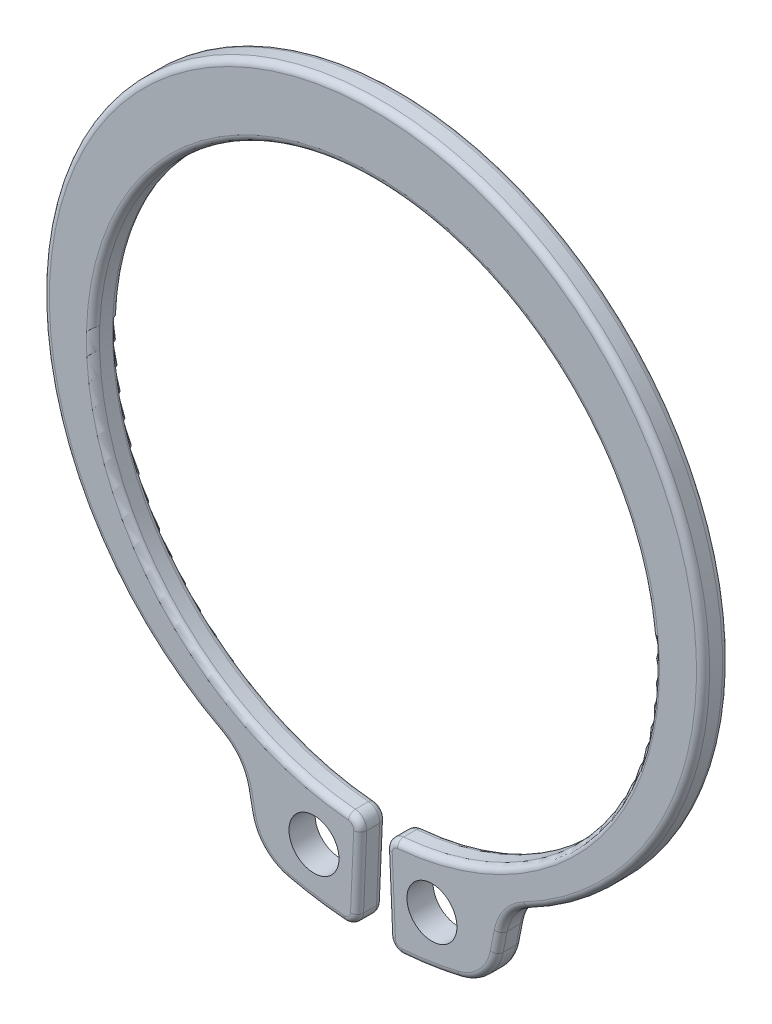
SolidWorks part; units mm, degrees
ref_plane "Front" through (0, 0, 0) normal (0, 0, 1) x (1, 0, 0)
ref_plane "Top" through (0, 0, 0) normal (0, 1, 0) x (1, 0, 0)
ref_plane "Right" through (0, 0, 0) normal (1, 0, 0) x (0, 0, -1)
sketch "Sketch1" plane through (0, 0, 0) normal (0, 0, 1) x (1, 0, 0)
  line L0 (0, 0) -> (-13.943, -8.05) construction
  line L1 (0, 21.7) -> (0, -21.7) construction
  line L2 (-6.7705, -20.6385) -> (-7.6186, -16.3634) construction
  line L3 (0, 0) -> (13.943, -8.05) construction
  line L4 (-7.6186, -16.3634) -> (-8.4416, -18.1312) construction
  line L5 (-7.6186, -16.3634) -> (0, 0) construction
  line L6 (0, 16.1) -> (0, 20) construction
  line L7 (0, 20) -> (0, 18.05) construction
  line L8 (0, -16.1) -> (0, -21.7) construction
  line L9 (-3.8953, -21.3685) -> (0, 0) construction
  line L10 (0, 0) -> (-0.9474, -21.7) construction
  line L11 (-6.7705, -20.6385) -> (0, 0) construction
  line L12 (-7.3603, -17.6655) -> (-8.8151, -15.7883) construction
  line L13 (-8.0877, -16.7269) -> (-7.6186, -16.3634) construction
  line L14 (-2.8873, -15.839) -> (-3.8953, -21.3685) construction
  line L15 (-3.3913, -18.6038) -> (-2.1616, -18.8279) construction
  arc A0 (0, 20) -> (-7.6186, -16.3634) centre (0, 1.0202) ccw construction
  circle A2 centre (0, 0) radius 20 construction
  arc A3 (-6.7705, -20.6385) -> (-0.9474, -21.7) centre (0, 0) ccw construction
  circle A4 centre (0, 0) radius 16.1 construction
  circle A6 centre (-3.3913, -18.6038) radius 1.25 construction
  arc A7 (-8.8151, -15.7883) -> (-7.3603, -17.6655) centre (-10.1425, -18.3194) cw construction
  point P5 (-13.943, -8.05)
  point P11 (13.943, -8.05)
  point P24 (-6.2342, -19.0036)
  point P35 (0, 20)
  point P36 (0, 16.1)
  point P37 (0, -16.1)
  point P38 (0, -21.7)
  dimension "Ring ID" = 32.2
  dimension "Hole Diameter" = 2.5
  dimension "D10" = 2.858
  dimension "Max Sec." = 3.9
  dimension "Lug Height" = 5.6
  dimension "D6" = 2.5
  dimension "D5" = 4.3584
  dimension "D8" = 2.375
  dimension "D3" = 120
  dimension "D7" = 60
  dimension "D2" = 5.9375
  dimension "D4" = 2.375
sketch "Sketch5" plane through (0, 0, 0) normal (0, 1, 0) x (1, 0, 0)
  line L0 (-20, 0.75) -> (-20, -0.75) construction
  line L2 (0, 0.75) -> (0, -0.75) construction
  line L4 (-20, 0) -> (20, 0) construction
  point P3 (-20, 0)
  point P6 (0, 0)
  dimension "Ring Thickness" = 1.5
sketch "Sketch2" plane through (0, 0, 0) normal (0, 0, 1) x (1, 0, 0)
  line L0 (-6.7705, -20.6385) -> (-7.6186, -16.3634) construction
  line L1 (-6.7705, -20.6385) -> (-7.6186, -16.3634)
  line L2 (0, 20) -> (0, 16.1)
  line L3 (-0.9474, -21.7) -> (-0.7023, -16.0847)
  line L4 (0, 0) -> (-0.9474, -21.7) construction
  arc A0 (0, 20) -> (-7.6186, -16.3634) centre (0, 1.0202) ccw construction
  arc A1 (-6.7705, -20.6385) -> (-0.9474, -21.7) centre (0, 0) ccw construction
  circle A2 centre (-3.3913, -18.6038) radius 1.25 construction
  circle A3 centre (-3.3913, -18.6038) radius 1.4375
  arc A4 (0, 20) -> (-7.6186, -16.3634) centre (0, 1.0202) ccw
  arc A5 (-6.7705, -20.6385) -> (-0.9474, -21.7) centre (0, 0) ccw
  circle A6 centre (-3.3913, -18.6038) radius 1.25 construction
  circle A7 centre (0, 0) radius 16.1 construction
  arc A8 (0, 16.1) -> (-0.7023, -16.0847) centre (0, 0) ccw
  dimension "D1" = 2.875
extrude "Boss-Extrude1" add sketch "Sketch2" along normal mid plane 1.5
fillet "Fillet1" radius 2.858 2 edges at (-7.6186, -16.3634, 0) (-6.7705, -20.6385, 0)
fillet "Fillet2" radius 0.7145 2 edges at (-0.9474, -21.7, 0) (-0.7023, -16.0847, 0)
mirror "Mirror1" about plane through (0, 20, 0.75) normal (-1, 0, 0) of bodies 109
fillet "Fillet3" radius 0.375 32 edges at (-0.9097, -16.2808, -0.75) (-0.8243, -18.8787, -0.75) (-1.1559, -21.4778, -0.75) (-3.3326, -21.4635, -0.75) (-6.3635, -20.3498, -0.75) (-7.2262, -18.3412, -0.75) (-7.8551, -16.6075, -0.75) (0, 20, -0.75) (7.8551, -16.6075, 0.75) (7.8551, -16.6075, -0.75) (7.2262, -18.3412, -0.75) (7.2262, -18.3412, 0.75) (6.3635, -20.3498, 0.75) (6.3635, -20.3498, -0.75) (3.3326, -21.4635, -0.75) (3.3326, -21.4635, 0.75) (1.1559, -21.4778, 0.75) (1.1559, -21.4778, -0.75) (0.8243, -18.8787, 0.75) (0.8243, -18.8787, -0.75) (0.9097, -16.2808, 0.75) (0.9097, -16.2808, -0.75) (-0.9097, -16.2808, 0.75) (-0.8243, -18.8787, 0.75) (-1.1559, -21.4778, 0.75) (-3.3326, -21.4635, 0.75) (-6.3635, -20.3498, 0.75) (-7.2262, -18.3412, 0.75) (-7.8551, -16.6075, 0.75) (0, 20, 0.75) (0, 16.1, -0.75) (0, 16.1, 0.75)
sketch "Sketch3" plane through (0, 0, 0.75) normal (0, 0, 1) x (1, 0, 0)
  line L0 (7.8955, -14.0311) -> (8.8168, -15.7874) construction
  line L1 (8.8168, -15.7874) -> (10.5731, -14.8661) construction
  line L2 (0, 20) -> (0, 16.1) construction
  circle A0 centre (0, 0) radius 16.1 construction
  arc A1 (-8.8168, -15.7874) -> (8.8168, -15.7874) centre (0, 1.0202) ccw construction
equation "\"Thickness@Boss-Extrude1\"=\"Ring Thickness@Sketch5\""
equation "\"D2@Sketch1\"=\"Hole Diameter@Sketch1\"*2.375"
equation "\"D4@Sketch1\"=\"D2@Sketch1\"/2.5"
equation "\"D8@Sketch1\"=\"D4@Sketch1\""
equation "\"D1@Sketch2\"=\"Hole Diameter@Sketch1\"*1.15"
equation "\"D1@Fillet2\"=\"D10@Sketch1\" / 4"
equation "\"D1@Fillet3\"=\"Ring Thickness@Sketch5\"/4"
equation "\"D1@Fillet1\"=\"D10@Sketch1\""
